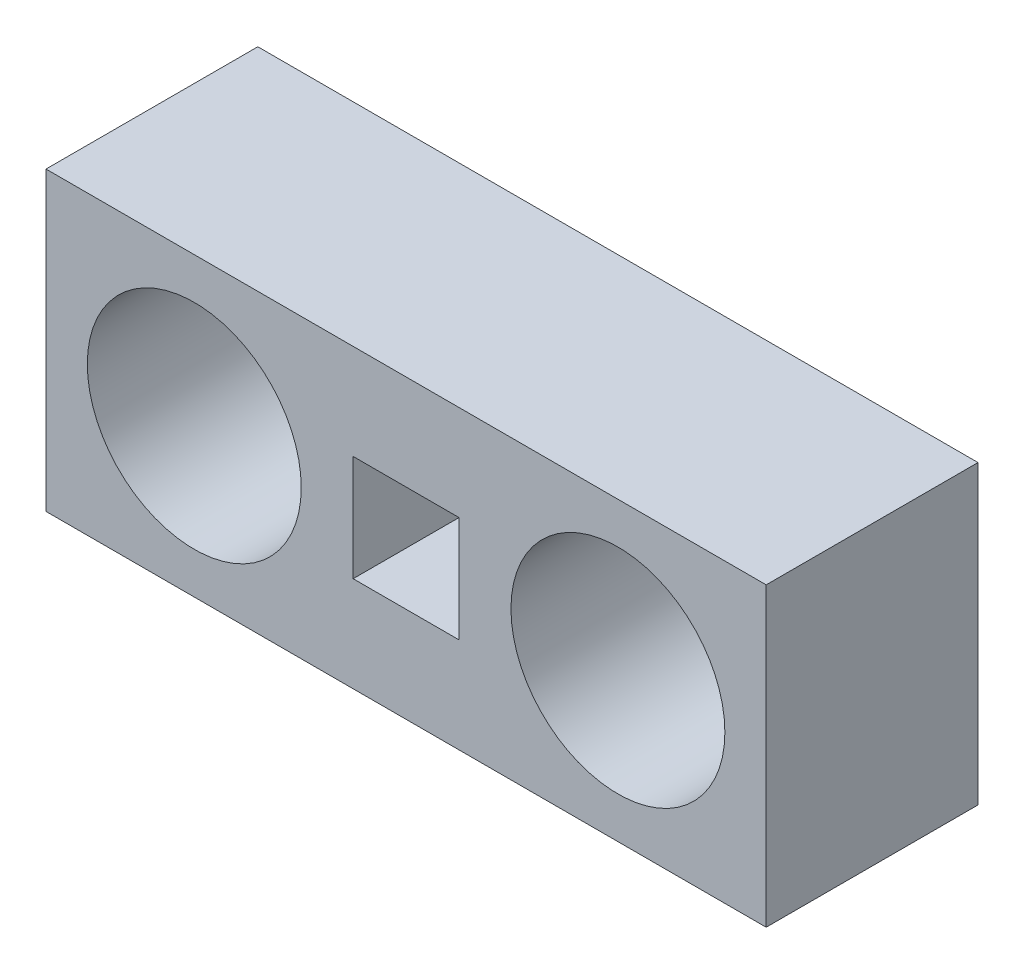
SolidWorks part; units mm, degrees
ref_plane "前视基准面" through (0, 0, 0) normal (0, 0, 1) x (1, 0, 0)
ref_plane "上视基准面" through (0, 0, 0) normal (0, 1, 0) x (1, 0, 0)
ref_plane "右视基准面" through (0, 0, 0) normal (1, 0, 0) x (0, 0, -1)
sketch "草图1" plane through (0, 0, 0) normal (0, 0, 1) x (1, 0, 0)
  line L0 (10, 0) -> (-10, 0) construction
  line L1 (-10, 0) -> (10, 0) construction
  line L2 (-10, 5.05) -> (10, 5.05) construction
  line L3 (-10, -5.05) -> (10, -5.05) construction
  line L5 (17, 7) -> (-17, 7)
  line L6 (17, 7) -> (17, -7)
  line L7 (17, -7) -> (-17, -7)
  line L8 (-17, 7) -> (-17, -7)
  line L9 (17, 7) -> (-17, -7) construction
  line L10 (17, -7) -> (-17, 7) construction
  line L11 (-2.5, 2.5) -> (2.5, 2.5)
  line L12 (-2.5, 2.5) -> (-2.5, -2.5)
  line L13 (-2.5, -2.5) -> (2.5, -2.5)
  line L14 (2.5, 2.5) -> (2.5, -2.5)
  line L15 (-2.5, 2.5) -> (2.5, -2.5) construction
  line L16 (-2.5, -2.5) -> (2.5, 2.5) construction
  arc A0 (-10, 5.05) -> (-10, -5.05) centre (-10, 0) ccw construction
  arc A1 (10, -5.05) -> (10, 5.05) centre (10, 0) ccw construction
  circle A2 centre (-10, 0) radius 5.05
  circle A3 centre (10, 0) radius 5.05
  point P0 (0, 0)
  point P3 (0, 0)
  point P4 (0, 0)
  point P18 (0, 0)
  dimension "D1" = 5.05
  dimension "D5" = 5
  dimension "D2" = 20
  dimension "D3" = 14
  dimension "D4" = 34
  dimension "D6" = 5
extrude "凸台-拉伸1" add sketch "草图1" along normal blind 10
